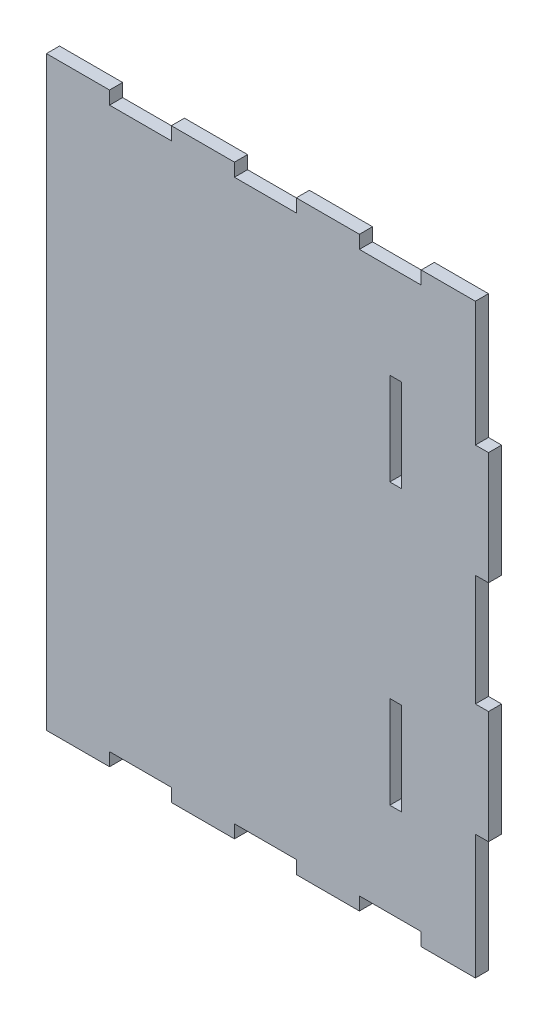
SolidWorks part; units mm, degrees
ref_plane "Front Plane" through (0, 0, 0) normal (0, 0, 1) x (1, 0, 0)
ref_plane "Top Plane" through (0, 0, 0) normal (0, 1, 0) x (1, 0, 0)
ref_plane "Right Plane" through (0, 0, 0) normal (1, 0, 0) x (0, 0, -1)
sketch "Sketch1" plane through (0, 0, 0) normal (0, 0, 1) x (1, 0, 0)
  line L0 (0, 38.592) -> (0, 13.064) construction
  line L1 (0, 13.064) -> (0, 12.764) construction
  line L2 (3, 38.592) -> (3, 64.12) construction
  line L3 (3, 64.12) -> (3, 67.12) construction
  line L4 (-97.9517, -64.12) -> (-98.2517, -64.12) construction
  line L5 (-83.7946, -64.12) -> (-97.9517, -64.12) construction
  line L6 (-26.566, -64.12) -> (-12.4088, -64.12)
  line L7 (-55.1803, -64.12) -> (-41.0231, -64.12)
  line L8 (-83.7946, -64.12) -> (-69.6374, -64.12)
  line L9 (-12.4088, -67.12) -> (-12.4088, -64.12)
  line L10 (0, -67.12) -> (-12.4088, -67.12)
  line L11 (-26.566, -64.12) -> (-26.566, -67.12)
  line L12 (-41.0231, -67.12) -> (-41.0231, -64.12)
  line L13 (-26.566, -67.12) -> (-41.0231, -67.12)
  line L14 (-55.1803, -64.12) -> (-55.1803, -67.12)
  line L15 (-69.6374, -67.12) -> (-69.6374, -64.12)
  line L16 (-55.1803, -67.12) -> (-69.6374, -67.12)
  line L17 (-83.7946, -64.12) -> (-83.7946, -67.12)
  line L18 (-83.7946, -67.12) -> (-98.2517, -67.12)
  line L19 (-16.9017, 42.6466) -> (-16.9017, 21.4733)
  line L20 (-16.9017, 42.6466) -> (-19.6017, 42.6466)
  line L21 (-16.9017, 21.4733) -> (-19.6017, 21.4733)
  line L22 (-19.6017, 42.6466) -> (-19.6017, 21.4733)
  line L23 (-18.2517, 42.6466) -> (-18.2517, 64.12) construction
  line L24 (-83.7946, 67.12) -> (-98.2517, 67.12)
  line L25 (-98.2517, 67.12) -> (-98.2517, -67.12)
  line L27 (-83.7946, 64.12) -> (-83.7946, 67.12)
  line L28 (-55.1803, 67.12) -> (-69.6374, 67.12)
  line L29 (-69.6374, 67.12) -> (-69.6374, 64.12)
  line L31 (-55.1803, 64.12) -> (-55.1803, 67.12)
  line L32 (-26.566, 67.12) -> (-41.0231, 67.12)
  line L33 (-41.0231, 67.12) -> (-41.0231, 64.12)
  line L35 (-26.566, 64.12) -> (-26.566, 67.12)
  line L36 (0, 67.12) -> (-12.4088, 67.12)
  line L37 (-12.4088, 67.12) -> (-12.4088, 64.12)
  line L40 (3, -12.764) -> (3, -38.592)
  line L41 (3, -38.592) -> (0, -38.592)
  line L43 (0, -12.764) -> (3, -12.764)
  line L44 (3, 38.592) -> (3, 12.764)
  line L45 (3, 12.764) -> (0, 12.764)
  line L47 (0, 38.592) -> (3, 38.592)
  line L48 (-83.7946, 64.12) -> (-69.6374, 64.12)
  line L49 (-55.1803, 64.12) -> (-41.0231, 64.12)
  line L50 (-26.566, 64.12) -> (-12.4088, 64.12)
  line L51 (0, 38.592) -> (0, 67.12)
  line L52 (0, 12.764) -> (0, -12.764)
  line L53 (0, -38.592) -> (0, -67.12)
  line L54 (65.8171, 0) -> (10.3368, 0) construction
  line L55 (-83.7946, 64.12) -> (-97.9517, 64.12) construction
  line L56 (-97.9517, 64.12) -> (-98.2517, 64.12) construction
  line L57 (-18.2517, 21.4733) -> (-18.2517, 0) construction
  line L58 (-18.2517, 21.4733) -> (-18.2517, 42.9466) construction
  line L59 (-18.2517, 42.9466) -> (-19.6017, 42.6466) construction
  line L60 (-16.9017, -21.4733) -> (-19.6017, -21.4733)
  line L61 (-19.6017, -42.6466) -> (-19.6017, -21.4733)
  line L62 (-16.9017, -42.6466) -> (-19.6017, -42.6466)
  line L63 (-16.9017, -42.6466) -> (-16.9017, -21.4733)
  point P7 (0, 0)
  point P50 (-98.2517, 0)
  point P56 (-24.1736, 21.5733)
  point P58 (0, 0)
  point P59 (-22.4376, 21.5733)
  point P60 (0, 0)
  point P61 (-30.307, 20.7607)
  point P62 (-30.1102, 45.0742)
  point P63 (-25.4936, 42.5466)
  dimension "D1" = 12.4088
  dimension "D2" = 0.3
  dimension "D3" = 98.2517
  dimension "D4" = 0.3
  dimension "D5" = 3
  dimension "D6" = 64.12
  dimension "D7" = 2.7
  dimension "D8" = 80
extrude "Boss-Extrude1" add sketch "Sketch1" along normal blind 3
